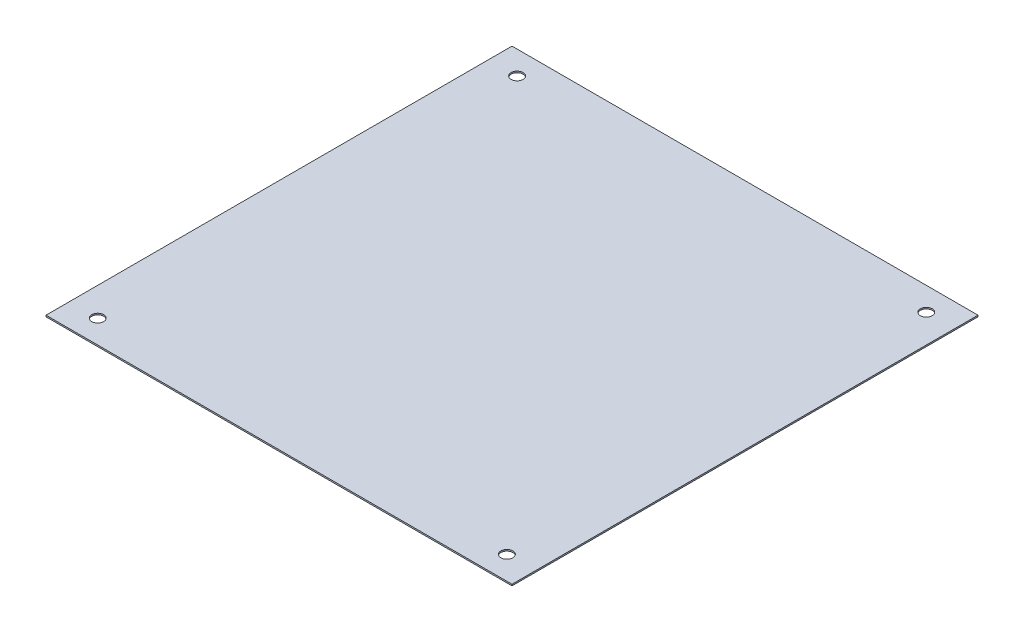
SolidWorks part; units mm, degrees
ref_plane "Front Plane" through (0, 0, 0) normal (0, 0, 1) x (1, 0, 0)
ref_plane "Top Plane" through (0, 0, 0) normal (0, 1, 0) x (1, 0, 0)
ref_plane "Right Plane" through (0, 0, 0) normal (1, 0, 0) x (0, 0, -1)
sketch "Sketch1" plane through (0, 0, 0) normal (0, 1, 0) x (1, 0, 0)
  line L0 (127, 254) -> (127, 241.3) construction
  line L1 (0, 0) -> (254, 0)
  line L2 (0, 0) -> (0, 254)
  line L3 (0, 254) -> (254, 254)
  line L4 (254, 0) -> (254, 254)
  line L5 (15.494, 12.7) -> (238.506, 12.7) construction
  line L6 (15.494, 12.7) -> (15.494, 241.3) construction
  line L7 (15.494, 241.3) -> (238.506, 241.3) construction
  line L8 (238.506, 12.7) -> (238.506, 241.3) construction
  line L9 (238.506, 127) -> (254, 127) construction
  circle A0 centre (15.494, 241.3) radius 3.2639
  circle A1 centre (238.506, 241.3) radius 3.2639
  circle A2 centre (238.506, 12.7) radius 3.2639
  circle A3 centre (15.494, 12.7) radius 3.2639
  dimension "D2" = 12.7
  dimension "D4" = 6.5278
  dimension "D1" = 254
  dimension "D3" = 15.494
extrude "Boss-Extrude1" add sketch "Sketch1" along normal blind 0.7937
